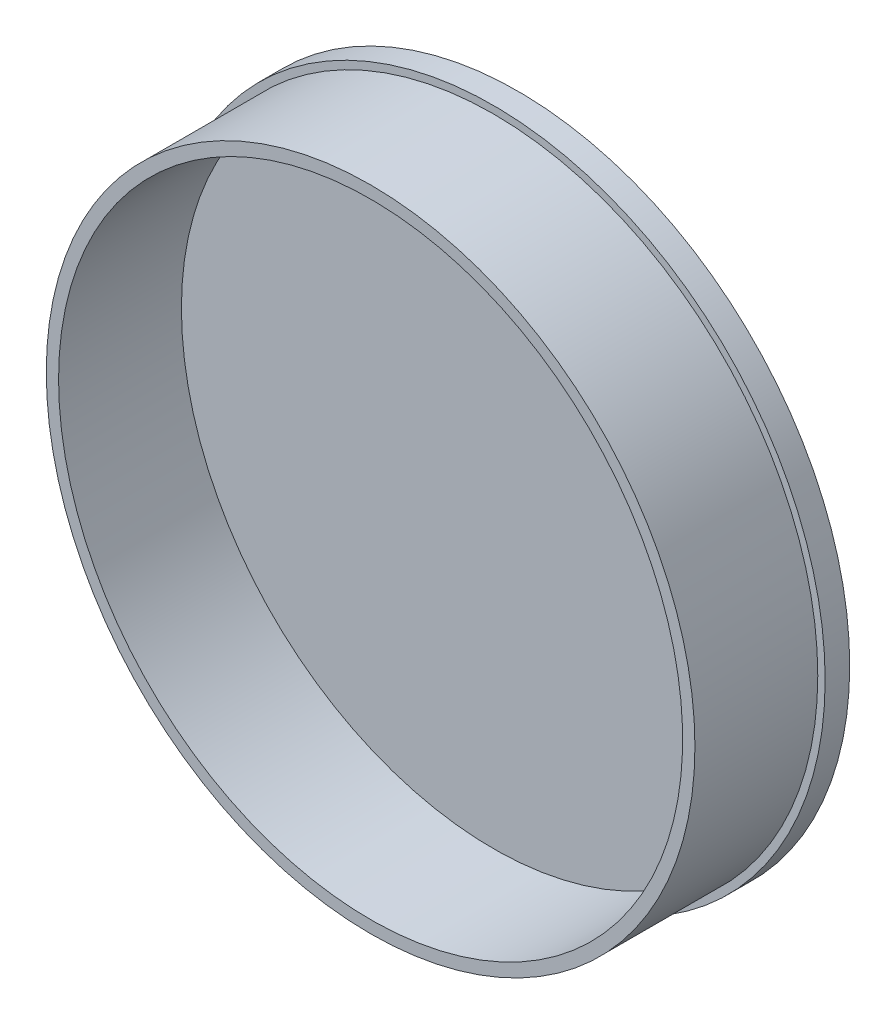
SolidWorks part; units mm, degrees
ref_plane "Front Plane" through (0, 0, 0) normal (0, 0, 1) x (1, 0, 0)
ref_plane "Top Plane" through (0, 0, 0) normal (0, 1, 0) x (1, 0, 0)
ref_plane "Right Plane" through (0, 0, 0) normal (1, 0, 0) x (0, 0, -1)
sketch "Sketch1" plane through (0, 0, 0) normal (0, 0, 1) x (1, 0, 0)
  circle A0 centre (0, 0) radius 135
extrude "Boss-Extrude1" add sketch "Sketch1" along normal mid plane 10
sketch "Sketch2" plane through (0, 0, 5) normal (0, 0, 1) x (1, 0, 0)
  circle A0 centre (0, 0) radius 132
  circle A1 centre (0, 0) radius 127
extrude "Boss-Extrude2" add sketch "Sketch2" along normal blind 50
